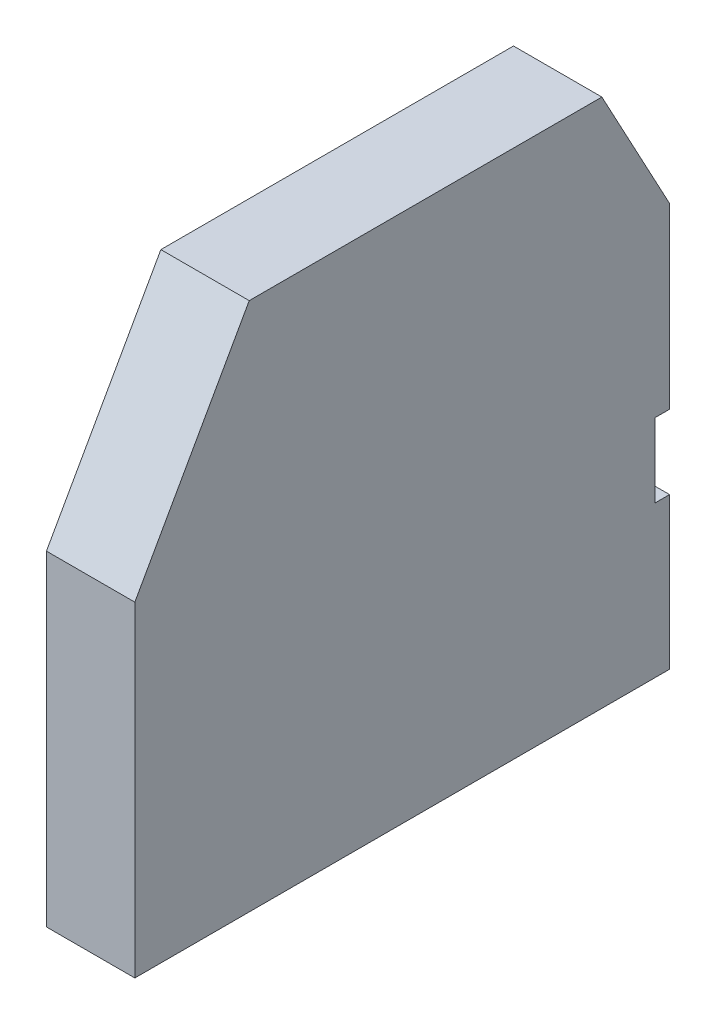
SolidWorks part; units mm, degrees
ref_plane "前视基准面" through (0, 0, 0) normal (0, 0, 1) x (1, 0, 0)
ref_plane "上视基准面" through (0, 0, 0) normal (0, 1, 0) x (1, 0, 0)
ref_plane "右视基准面" through (0, 0, 0) normal (1, 0, 0) x (0, 0, -1)
sketch "草图1" plane through (0, 0, 0) normal (0, 1, 0) x (1, 0, 0)
  line L0 (0, 11.8686) -> (0, -8.9519) construction
  line L1 (-1, 6.05) -> (1, 6.05)
  line L2 (-1, 6.05) -> (-1, -6.05)
  line L3 (-1, -6.05) -> (1, -6.05)
  line L4 (1, 6.05) -> (1, -6.05)
  line L5 (-7.6731, 0) -> (6.4167, 0) construction
  point P4 (-1, 0)
  dimension "D1" = 2
  dimension "D2" = 12.1
extrude "凸台-拉伸1" add sketch "草图1" along normal blind 13.2
sketch "草图2" plane through (-1, 0, 0) normal (-1, 0, 0) x (0, 0, 1)
  line L0 (-6.05, 13.2) -> (-6.05, 0) construction
  line L1 (-6.05, 5.0954) -> (-5.7193, 5.0954)
  line L2 (-6.05, 5.0954) -> (-6.05, 3.4236)
  line L3 (-6.05, 3.4236) -> (-5.7193, 3.4236)
  line L4 (-5.7193, 5.0954) -> (-5.7193, 3.4236)
  line L5 (-4.5187, 11.98) -> (-6.05, 9.1297)
  line L6 (-4.5187, 11.98) -> (3.4614, 11.98)
  line L7 (-6.05, 13.2) -> (6.05, 13.2)
  line L8 (-6.05, 13.2) -> (6.05, 13.2) construction
  line L9 (-6.05, 9.1297) -> (-6.05, 13.2)
  line L12 (6.05, 13.2) -> (6.05, 0) construction
  line L14 (6.05, 7.3656) -> (6.05, 13.2)
  line L18 (3.4614, 11.98) -> (6.05, 7.3656)
  dimension "D1" = 28.247
  dimension "D2" = 4.0703
  dimension "D3" = 29.291
  dimension "D4" = 5.8344
  dimension "D5" = 1.22
extrude "切除-拉伸1" cut sketch "草图2" against normal blind 13.2
